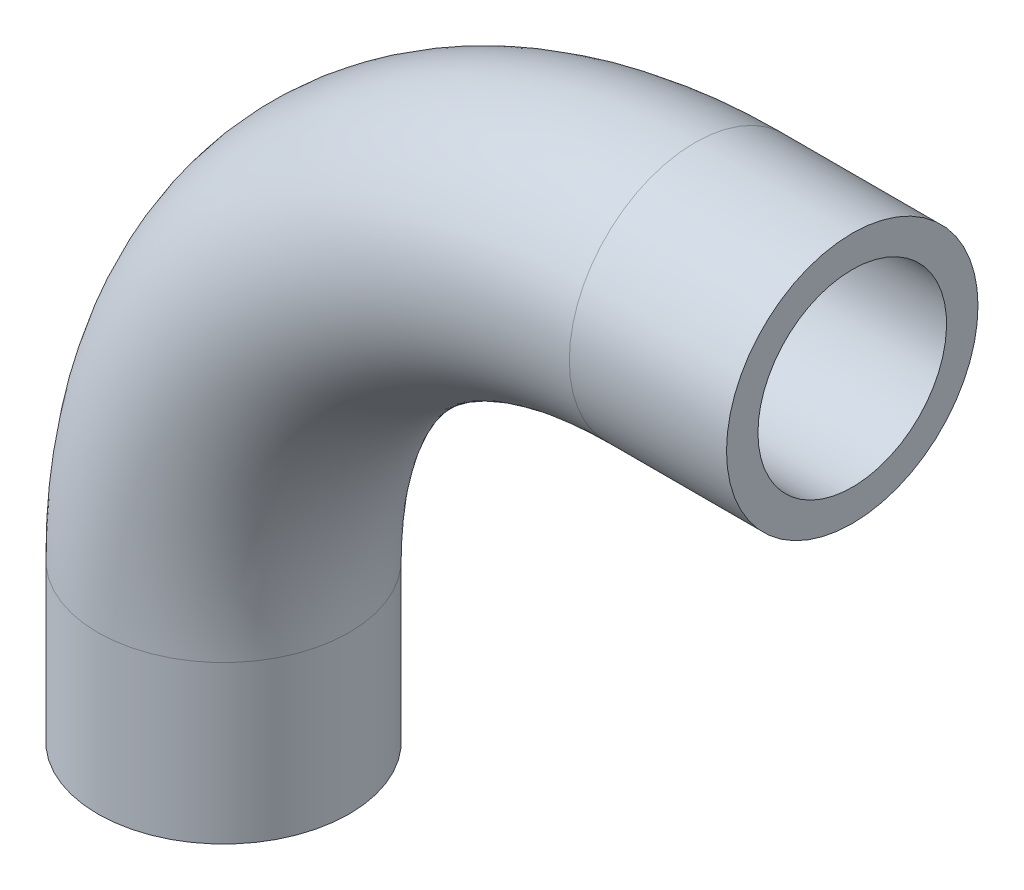
SolidWorks part; units mm, degrees
ref_plane "Front Plane" through (0, 0, 0) normal (0, 0, 1) x (1, 0, 0)
ref_plane "Top Plane" through (0, 0, 0) normal (0, 1, 0) x (1, 0, 0)
ref_plane "Right Plane" through (0, 0, 0) normal (1, 0, 0) x (0, 0, -1)
sketch "Sketch1" plane through (0, 0, 0) normal (0, 0, 1) x (1, 0, 0)
  line L0 (0, 0) -> (0, 5)
  line L1 (15, 20) -> (20, 20)
  arc A0 (0, 5) -> (15, 20) centre (15, 5) cw
  point P6 (0, 20)
  dimension "D3" = 15
  dimension "D1" = 20
  dimension "D2" = 20
  dimension "D4" = 90
sketch "Sketch2" plane through (0, 0, 0) normal (0, 1, 0) x (1, 0, 0)
  circle A0 centre (0, 0) radius 4
  circle A1 centre (0, 0) radius 3
  dimension "D1" = 6
  dimension "D2" = 8
sweep "Sweep1" add profiles "Sketch2" path "Sketch1"
